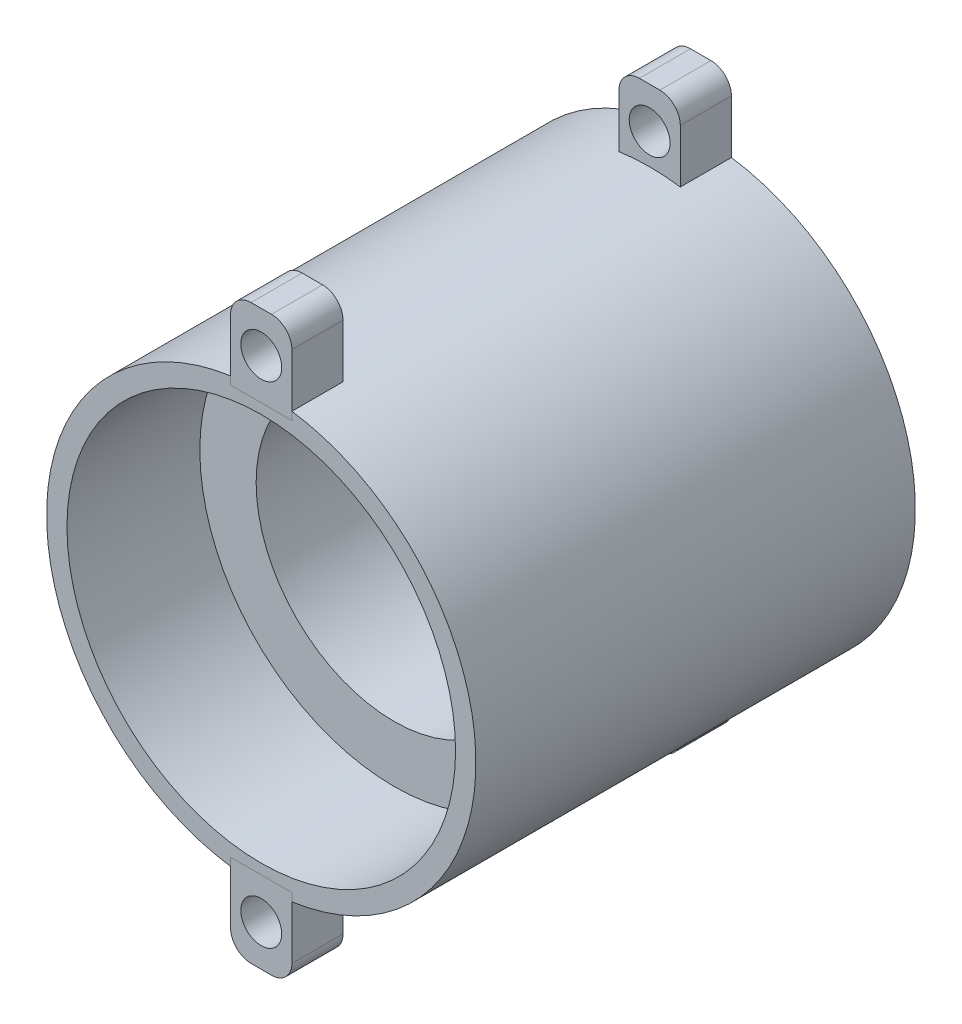
SolidWorks part; units mm, degrees
ref_plane "Front Plane" through (0, 0, 0) normal (0, 0, 1) x (1, 0, 0)
ref_plane "Top Plane" through (0, 0, 0) normal (0, 1, 0) x (1, 0, 0)
ref_plane "Right Plane" through (0, 0, 0) normal (1, 0, 0) x (0, 0, -1)
sketch "Sketch1" plane through (0, 0, 0) normal (0, 0, 1) x (1, 0, 0)
  circle A0 centre (0, 0) radius 13.5
  circle A1 centre (0, 0) radius 19.01
extrude "Boss-Extrude1" add sketch "Sketch1" along normal blind 30
sketch "Sketch2" plane through (0, 0, 30) normal (0, 0, 1) x (1, 0, 0)
  circle A0 centre (0, 0) radius 21
  circle A1 centre (0, 0) radius 19.01
extrude "Boss-Extrude2" add sketch "Sketch2" along normal blind 13 and the other way blind 30
sketch "Sketch3" plane through (0, 0, 0) normal (0, 0, -1) x (-1, 0, 0)
  line L0 (12.8914, 5.46) -> (17.4939, 7.4137)
  line L1 (15.5403, 12.0162) -> (10.9378, 10.0625)
  line L2 (15.5403, 12.0162) -> (19.4476, 2.8111)
  line L3 (19.4476, 2.8111) -> (14.8451, 0.8575)
  line L4 (10.9378, 10.0625) -> (14.8451, 0.8575)
  circle A0 centre (0, 0) radius 13.5 construction
  point P2 (12.8914, 5.46)
  point P6 (17.4939, 7.4137)
  dimension "D1" = 14
  dimension "D2" = 5.46
extrude "Cut-Extrude1" cut sketch "Sketch3" against normal offset from surface (28 mm away) 2 contours L1 L4 L3 L2 up to face at (19.01, 0, 30)
mirror "Mirror1" about plane through (0, 0, 0) normal (0, 1, 0) of "Cut-Extrude1"
mirror "Mirror2" about plane through (0, 0, 0) normal (1, 0, 0) of "Mirror1", "Cut-Extrude1"
sketch "Sketch4" plane through (0, 0, 0) normal (0, 0, -1) x (-1, 0, 0)
  line L1 (-3, 28) -> (3, 28)
  line L2 (-3, 28) -> (-3, 20)
  line L3 (-3, 20) -> (3, 20)
  line L4 (3, 28) -> (3, 20)
  circle A0 centre (0, 24) radius 2
  point P4 (0, 20)
  dimension "D1" = 4
  dimension "D2" = 20
extrude "Boss-Extrude3" add sketch "Sketch4" along normal blind 0.0001 and the other way blind 5
fillet "Fillet1" radius 2 2 edges at (3, 28, 2.5) (-3, 28, 2.5)
mirror "Mirror5" about plane through (0, 0, 0) normal (0, 1, 0) of "Fillet1", "Boss-Extrude3"
sketch "Sketch7" plane through (0, 0, 43) normal (0, 0, 1) x (1, 0, 0)
  line L1 (-3, 28) -> (3, 28)
  line L2 (-3, 28) -> (-3, 20)
  line L3 (-3, 20) -> (3, 20)
  line L4 (3, 28) -> (3, 20)
  circle A0 centre (0, 24) radius 2
  point P4 (0, 20)
  dimension "D1" = 20
  dimension "D2" = 4
extrude "Boss-Extrude6" add sketch "Sketch7" along normal blind 0.0001 and the other way blind 5
mirror "Mirror6" about plane through (0, 0, 0) normal (0, 1, 0) of "Boss-Extrude6"
fillet "Fillet2" radius 2 4 edges at (-3, 28, 40.5) (3, 28, 40.5) (3, -28, 40.5) (-3, -28, 40.5)
